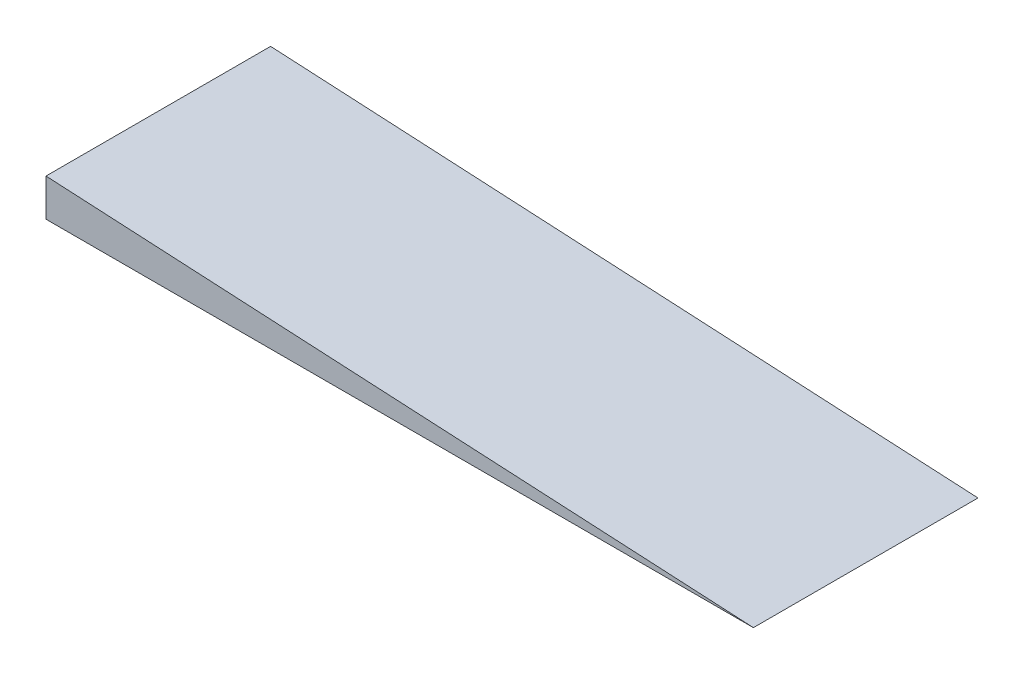
SolidWorks part; units mm, degrees
material "Plain Carbon Steel"
ref_plane "Front Plane" through (0, 0, 0) normal (0, 0, 1) x (1, 0, 0)
ref_plane "Top Plane" through (0, 0, 0) normal (0, 1, 0) x (1, 0, 0)
ref_plane "Right Plane" through (0, 0, 0) normal (1, 0, 0) x (0, 0, -1)
sketch "Sketch1" plane through (0, 0, 0) normal (0, 0, 1) x (1, 0, 0)
  line L0 (0, 0) -> (60, 0)
  line L1 (60, 0) -> (0, 3.175)
  line L2 (0, 3.175) -> (0, 0)
  dimension "D1" = 60
  dimension "D2" = 3.175
extrude "Boss-Extrude1" add sketch "Sketch1" along normal blind 19.05
